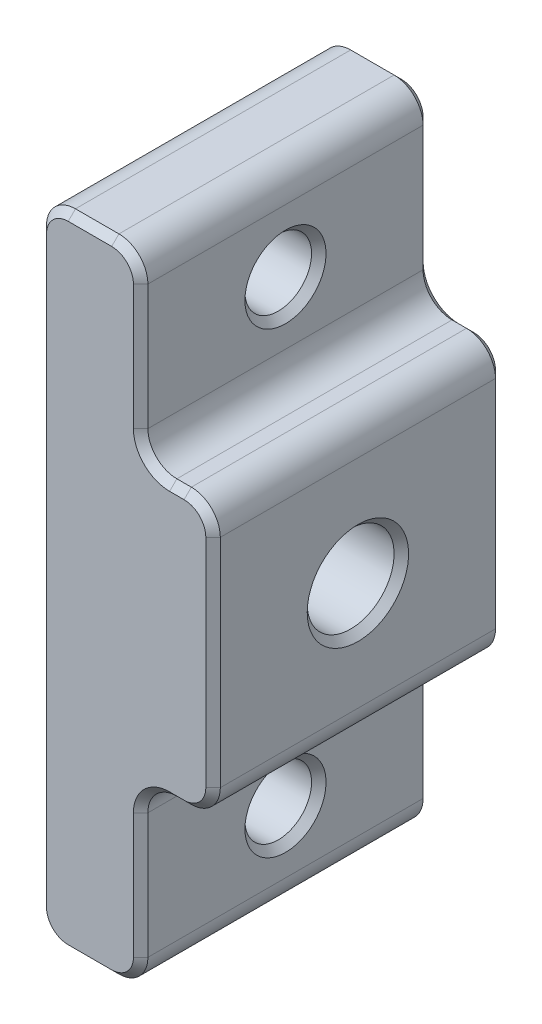
SolidWorks part; units mm, degrees
ref_plane "Front" through (0, 0, 0) normal (0, 0, 1) x (1, 0, 0)
ref_plane "Top" through (0, 0, 0) normal (0, 1, 0) x (1, 0, 0)
ref_plane "Right" through (0, 0, 0) normal (1, 0, 0) x (0, 0, -1)
sketch "Skizze1" plane through (0, 0, 0) normal (0, 0, 1) x (1, 0, 0)
  line L0 (0, 0) -> (19.3854, 0) construction
  line L1 (0, -22.1303) -> (0, 22.1303)
  line L2 (0, 22.1303) -> (7, 22.1303)
  line L3 (7, 22.1303) -> (7, 9.4858)
  line L4 (7, 9.4858) -> (12, 9.4858)
  line L5 (12, 9.4858) -> (12, -9.4858)
  line L6 (7, -9.4858) -> (12, -9.4858)
  line L7 (7, -22.1303) -> (7, -9.4858)
  line L8 (0, -22.1303) -> (7, -22.1303)
  point P9 (12, 0)
  dimension "D1" = 7
  dimension "D2" = 12
extrude "Aufsatz-Linear austragen1" add sketch "Skizze1" along normal blind 20
sketch "Skizze2" plane through (12, 0, 0) normal (1, 0, 0) x (0, 0, -1)
  line L0 (0, 0) -> (-20, 0) construction
  line L1 (-20, -9.4858) -> (-20, 9.4858) construction
  circle A0 centre (-10, 0) radius 3
  dimension "D1" = 6
extrude "Schnitt-Linear austragen1" cut sketch "Skizze2" against normal blind 20
sketch "Skizze3" plane through (0, 0, 0) normal (-1, 0, 0) x (0, 0, 1)
  circle A0 centre (10, 0) radius 5.25
  dimension "D1" = 10.5
extrude "Schnitt-Linear austragen2" cut sketch "Skizze3" against normal blind 6.55
sketch "Skizze4" plane through (7, 0, 0) normal (1, 0, 0) x (0, 0, -1)
  line L0 (-10, -9.4858) -> (-10, -22.1303) construction
  line L1 (-20, -9.4858) -> (0, -9.4858) construction
  line L2 (-20, -22.1303) -> (0, -22.1303) construction
  line L3 (0, 0) -> (-20, 0) construction
  line L4 (-20, -9.4858) -> (-20, 9.4858) construction
  circle A0 centre (-10, -15.8081) radius 2.3
  circle A1 centre (-10, 15.8081) radius 2.3
  dimension "D1" = 4.6
extrude "Schnitt-Linear austragen3" cut sketch "Skizze4" against normal blind 10
fillet "Verrundung1" radius 2 8 edges at (0, 22.1303, 10) (7, -9.4858, 10) (7, 22.1303, 10) (7, 9.4858, 10) (12, 9.4858, 10) (12, -9.4858, 10) (7, -22.1303, 10) (0, -22.1303, 10)
chamfer "Fase1" distance 0.5 angle 45 39 edges at (0, 15.8081, 7.7) (7, 15.8081, 12.3) (6.55, 0, 13) (12, 0, 7) (0, -15.8081, 7.7) (7, -15.8081, 7.7) (7, -15.8081, 20) (3.5, -22.1303, 20) (0, 0, 20) (3.5, 22.1303, 20) (7, 15.8081, 20) (9.5, 9.4858, 20) (12, 0, 20) (9.5, -9.4858, 20) (12, 0, 0) (9.5, 9.4858, 0) (7, 15.8081, 0) (3.5, 22.1303, 0) (0, 0, 0) (3.5, -22.1303, 0) (7, -15.8081, 0) (9.5, -9.4858, 0) (0, 0, 15.25) (6.4142, 21.5445, 20) (7.5858, 10.0716, 20) (11.4142, 8.9, 20) (11.4142, -8.9, 20) (7.5858, -10.0716, 20) (6.4142, -21.5445, 20) (0.5858, -21.5445, 20) (0.5858, 21.5445, 20) (0.5858, -21.5445, 0) (6.4142, -21.5445, 0) (7.5858, -10.0716, 0) (11.4142, -8.9, 0) (11.4142, 8.9, 0) (7.5858, 10.0716, 0) (6.4142, 21.5445, 0) (0.5858, 21.5445, 0)
